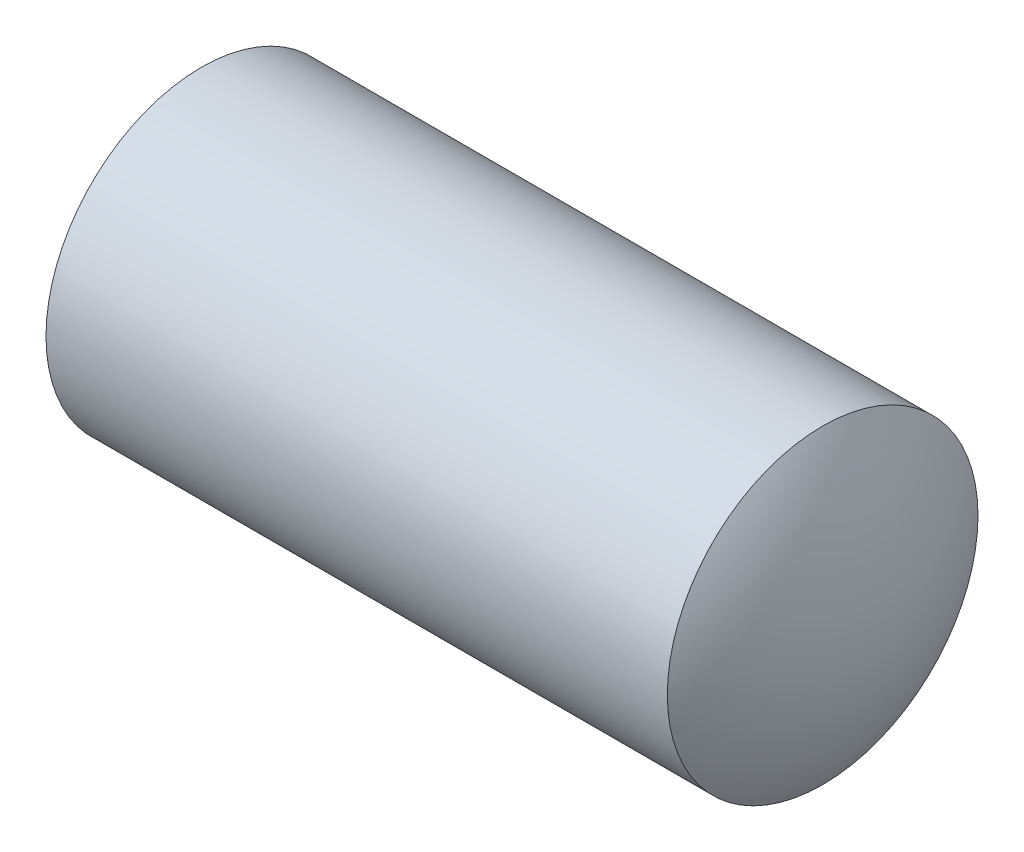
SolidWorks part; units mm, degrees
ref_plane "Front Plane" through (0, 0, 0) normal (0, 0, 1) x (1, 0, 0)
ref_plane "Top Plane" through (0, 0, 0) normal (0, 1, 0) x (1, 0, 0)
ref_plane "Right Plane" through (0, 0, 0) normal (1, 0, 0) x (0, 0, -1)
sketch "Sketch1" plane through (0, 0, 0) normal (0, 0, 1) x (1, 0, 0)
  line L0 (0, 0) -> (0.3, 0)
  line L1 (0.3, 0) -> (4.3, 0)
  line L2 (4.3, 0) -> (4.6, 0)
  line L3 (0.3, 0) -> (0.3, 1) construction
  line L4 (4.3, 0) -> (4.3, 1) construction
  line L5 (0.3, 1) -> (4.3, 1)
  line L6 (2.3, 0) -> (2.3, 1) construction
  arc A0 (0, 0) -> (0.3, 1) centre (1.8167, 0) cw
  arc A1 (4.6, 0) -> (4.3, 1) centre (2.7833, 0) ccw
  dimension "D1" = 0.3
  dimension "D2" = 4
  dimension "D3" = 1
revolve "Revolve1" add sketch "Sketch1" angle 360 about L1
ref_plane "Plane1" through (2.3, 0, 0) normal (1, 0, 0) x (0, 0, -1)
